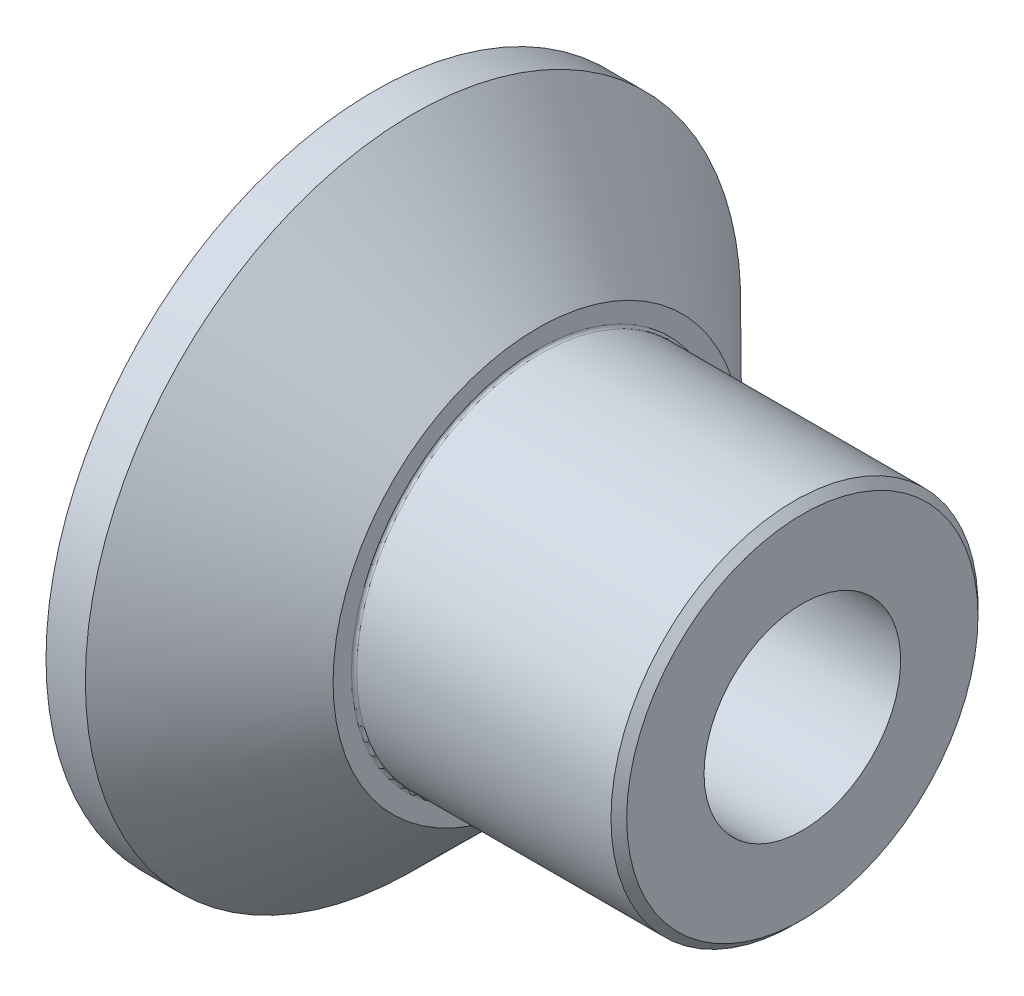
SolidWorks part; units mm, degrees
material "ZG10Cr13Ni1"
ref_plane "前视基准面" through (0, 0, 0) normal (0, 0, 1) x (1, 0, 0)
ref_plane "上视基准面" through (0, 0, 0) normal (0, 1, 0) x (1, 0, 0)
ref_plane "右视基准面" through (0, 0, 0) normal (1, 0, 0) x (0, 0, -1)
sketch "草图1" plane through (0, 0, 0) normal (0, 0, 1) x (1, 0, 0)
  line L0 (0, 0) -> (-120.5, 0)
  line L1 (-120.5, 0) -> (-120.5, 17.5)
  line L2 (-120.5, 17.5) -> (-163.5, 72.5)
  line L3 (-163.5, 72.5) -> (-163.5, 87.5)
  line L4 (-163.5, 87.5) -> (-148.5, 87.5)
  line L5 (-148.5, 87.5) -> (-101, 40.5)
  line L6 (-101, 40.5) -> (-101, 32.5)
  line L7 (-101, 32.5) -> (0, 32.5)
  line L8 (0, 32.5) -> (0, 0)
  line L9 (-120.5, -37.5) -> (0, -37.5) construction
  dimension "D1" = 15
  dimension "D2" = 110
  dimension "D3" = 250
  dimension "D4" = 43
  dimension "D5" = 120.5
  dimension "D6" = 140
  dimension "D7" = 101
  dimension "D8" = 8
  dimension "D9" = 75
revolve "旋转1" add sketch "草图1" angle 360 about L9
fillet "圆角1" radius 1 1 edges at (-101, -37.5, 70)
chamfer "倒角1" distance 3 angle 45 1 edges at (0, -37.5, 70)
